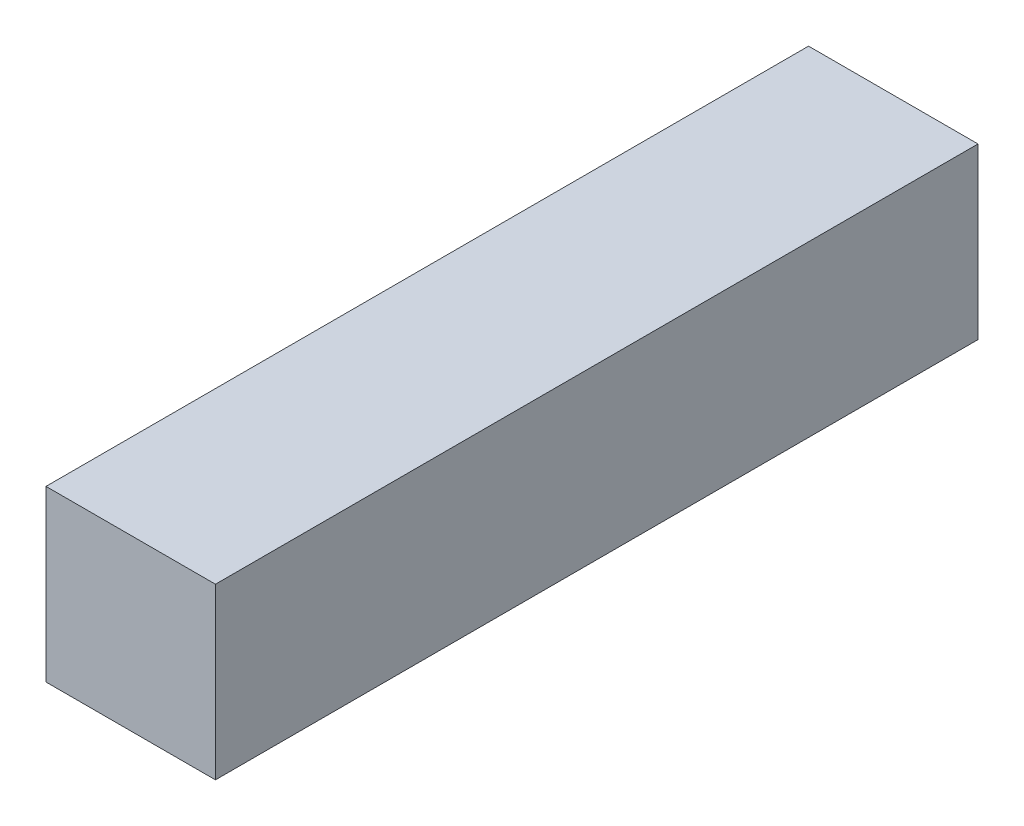
SolidWorks part; units mm, degrees
material "Plain Carbon Steel"
ref_plane "Front Plane" through (0, 0, 0) normal (0, 0, 1) x (1, 0, 0)
ref_plane "Top Plane" through (0, 0, 0) normal (0, 1, 0) x (1, 0, 0)
ref_plane "Right Plane" through (0, 0, 0) normal (1, 0, 0) x (0, 0, -1)
sketch "Sketch1" plane through (0, 0, 0) normal (0, 0, 1) x (1, 0, 0)
  line L1 (1.5875, -1.5875) -> (-1.5875, -1.5875)
  line L2 (1.5875, -1.5875) -> (1.5875, 1.5875)
  line L3 (1.5875, 1.5875) -> (-1.5875, 1.5875)
  line L4 (-1.5875, -1.5875) -> (-1.5875, 1.5875)
  line L5 (1.5875, -1.5875) -> (-1.5875, 1.5875) construction
  line L6 (1.5875, 1.5875) -> (-1.5875, -1.5875) construction
  point P0 (0, 0)
  dimension "D1" = 3.175
extrude "Boss-Extrude1" add sketch "Sketch1" along normal mid plane 14.2875
